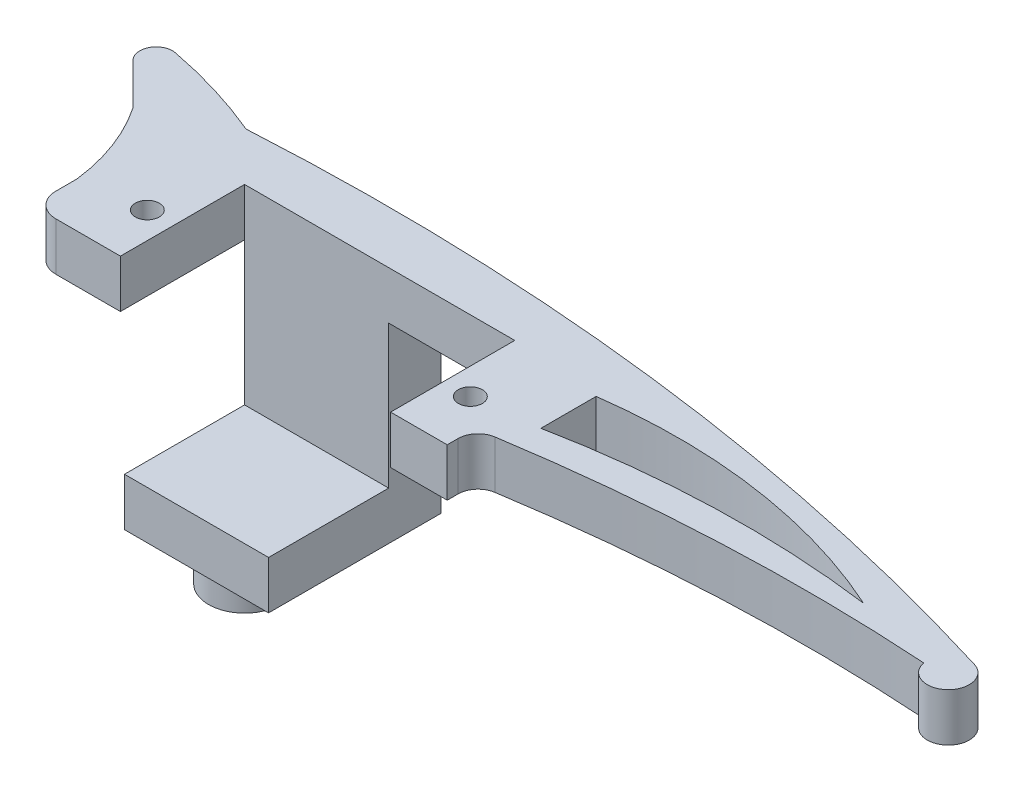
SolidWorks part; units mm, degrees
ref_plane "Front Plane" through (0, 0, 0) normal (0, 0, 1) x (1, 0, 0)
ref_plane "Top Plane" through (0, 0, 0) normal (0, 1, 0) x (1, 0, 0)
ref_plane "Right Plane" through (0, 0, 0) normal (1, 0, 0) x (0, 0, -1)
sketch "Sketch1" plane through (0, 0, 0) normal (0, 1, 0) x (1, 0, 0)
  line L0 (0, 0) -> (78.5, 0) construction
  line L1 (14, 0) -> (14, 5.9)
  line L2 (14, 5.9) -> (36.5, 5.9)
  line L3 (36.5, 5.9) -> (36.5, 0)
  line L4 (36.5, 0) -> (36.5, -4.4385)
  line L5 (36.5, -4.4385) -> (41.2135, -4.4385)
  line L6 (41.2135, -4.4385) -> (41.2135, -3.5362)
  line L7 (14, 0) -> (14, -4.4385)
  line L8 (14, -4.4385) -> (8.6263, -4.4385)
  line L9 (6.6263, -2.4385) -> (6.6263, -0.6969)
  line L10 (0, 0) -> (0, 19.9753) construction
  line L11 (0.3995, 10.2103) -> (3.8219, 6.7879)
  line L12 (43.9243, 5.25) -> (43.9243, 0.65)
  circle A0 centre (11.8, 0) radius 1
  circle A1 centre (38.7, 0) radius 1
  arc A2 (76.7808, -0.327) -> (79.0134, 1.673) centre (78.5, 0) ccw
  arc A3 (42.6218, -1.8878) -> (76.7808, -0.327) centre (66.695, -154.1701) cw
  arc A4 (79.0134, 1.673) -> (10.0717, 9.9549) centre (21.5542, -185.5486) ccw
  arc A5 (1.6203, 12.5146) -> (0.3995, 10.2103) centre (1.3641, 11.1748) ccw
  arc A6 (10.0717, 9.9549) -> (1.6203, 12.5146) centre (-6.2837, -28.8142) ccw
  arc A7 (3.8219, 6.7879) -> (6.6263, -0.6969) centre (-10.1705, -2.7226) cw
  arc A8 (8.6263, -4.4385) -> (6.6263, -2.4385) centre (8.6263, -2.4385) cw
  arc A9 (41.2135, -3.5362) -> (42.6218, -1.8878) centre (42.8824, -3.5362) cw
  arc A10 (43.9243, 0.65) -> (69.9814, 1.4684) centre (59.4329, -77.9048) cw
  arc A11 (69.9814, 1.4684) -> (43.9243, 5.25) centre (50.3928, -41.8431) ccw
  circle A14 centre (19.9, 0) radius 3 construction
  point P3 (14, 0)
  point P4 (36.5, 0)
  point P37 (36.5, 2.95)
  point P38 (43.9243, 2.95)
  point P42 (19.9, 0)
  dimension "D3" = 2
  dimension "D8" = 3.5
  dimension "D10" = 2
  dimension "D11" = 1.6689
  dimension "D14" = 6
  dimension "D1" = 78.5
  dimension "D2" = 22.5
  dimension "D4" = 2.2
  dimension "D5" = 2.2
  dimension "D6" = 14
  dimension "D7" = 5.9
  dimension "D9" = 2
  dimension "D12" = 4.6
  dimension "D13" = 5.9
extrude "Boss-Extrude1" add sketch "Sketch1" along normal mid plane 4
sketch "Sketch2" plane through (0, 2, 0) normal (0, 1, 0) x (1, 0, 0)
  line L3 (14, 5.9) -> (14, 10.1461)
  line L4 (26, 5.9) -> (26, 10.2414)
  line L10 (14, -4.4385) -> (14, 5.9)
  line L11 (14, 5.9) -> (36.5, 5.9)
  line L12 (36.5, 5.9) -> (36.5, -4.4385)
  line L13 (36.5, -4.4385) -> (41.2135, -4.4385)
  line L14 (41.2135, -4.4385) -> (41.2135, -3.5362)
  line L15 (0.3995, 10.2103) -> (3.8219, 6.7879)
  line L16 (6.6263, -0.6969) -> (6.6263, -2.4385)
  line L17 (8.6263, -4.4385) -> (14, -4.4385)
  line L19 (14, 5.9) -> (26, 5.9)
  arc A8 (42.6218, -1.8878) -> (41.2135, -3.5362) centre (42.8824, -3.5362) ccw
  arc A9 (76.7808, -0.327) -> (42.6218, -1.8878) centre (66.695, -154.1701) ccw
  arc A10 (76.7808, -0.327) -> (79.0134, 1.673) centre (78.5, 0) ccw
  arc A11 (79.0134, 1.673) -> (10.0717, 9.9549) centre (21.5542, -185.5486) ccw
  arc A12 (10.0717, 9.9549) -> (1.6203, 12.5146) centre (-6.2837, -28.8142) ccw
  arc A13 (1.6203, 12.5146) -> (0.3995, 10.2103) centre (1.3641, 11.1748) ccw
  arc A14 (6.6263, -0.6969) -> (3.8219, 6.7879) centre (-10.1705, -2.7226) ccw
  arc A15 (6.6263, -2.4385) -> (8.6263, -4.4385) centre (8.6263, -2.4385) ccw
  arc A19 (26, 10.2414) -> (14, 10.1461) centre (21.5542, -185.5486) ccw
  dimension "D1" = 0
extrude "Boss-Extrude2" add sketch "Sketch2" against normal blind 15.9 from surface at -4 starting at face at (11.8, -2, 1)
sketch "Sketch3" plane through (0, 0, -5.9) normal (0, 0, 1) x (1, 0, 0)
  line L1 (14, -13.9) -> (26, -13.9)
  line L7 (26, -2) -> (36.5, -2)
  line L8 (36.5, -2) -> (36.5, 2)
  line L9 (36.5, 2) -> (14, 2)
  line L10 (26, -17.9) -> (26, -2)
  line L11 (14, -17.9) -> (26, -17.9)
  line L12 (14, -2) -> (14, -17.9)
  line L13 (14, 2) -> (14, -2)
  line L17 (26, -17.9) -> (26, -13.9)
  line L18 (14, -17.9) -> (26, -17.9)
  line L19 (14, -13.9) -> (14, -17.9)
  dimension "D2" = 4
  dimension "D1" = 0
extrude "Boss-Extrude3" add sketch "Sketch3" along normal blind 10
sketch "Sketch5" plane through (0, -17.9, 0) normal (0, -1, 0) x (-1, 0, 0)
  circle A5 centre (-19.9, 0) radius 3 construction
  circle A6 centre (-19.9, 0) radius 3
extrude "Boss-Extrude4" add sketch "Sketch5" along normal blind 3
